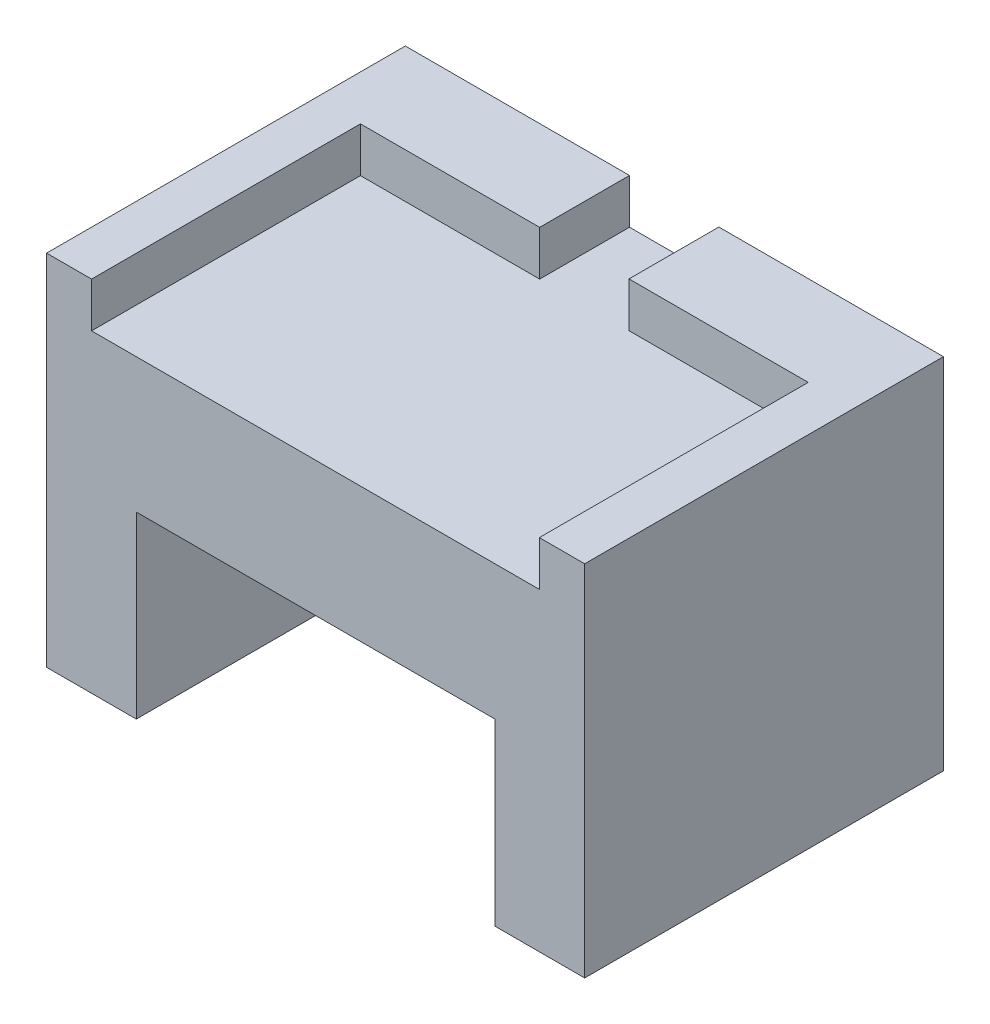
SolidWorks part; units mm, degrees
ref_plane "Front Plane" through (0, 0, 0) normal (0, 0, 1) x (1, 0, 0)
ref_plane "Top Plane" through (0, 0, 0) normal (0, 1, 0) x (1, 0, 0)
ref_plane "Right Plane" through (0, 0, 0) normal (1, 0, 0) x (0, 0, -1)
sketch "Sketch2" plane through (0, 0, 0) normal (0, 0, 1) x (1, 0, 0)
  line L1 (-7.9809, 8.5014) -> (68.2191, 8.5014)
  line L2 (-7.9809, 8.5014) -> (-7.9809, -16.8986)
  line L3 (-7.9809, -16.8986) -> (68.2191, -16.8986)
  line L4 (68.2191, 8.5014) -> (68.2191, -16.8986)
  dimension "D1" = 25.4
  dimension "D2" = 76.2
extrude "Boss-Extrude1" add sketch "Sketch2" along normal blind 50.8
sketch "Sketch3" plane through (0, -16.8986, 0) normal (0, -1, 0) x (1, 0, 0)
  line L0 (-7.9809, 0) -> (68.2191, 0) construction
  line L1 (-7.9809, 50.8) -> (4.7191, 50.8)
  line L2 (-7.9809, 50.8) -> (-7.9809, 0)
  line L3 (-7.9809, 0) -> (4.7191, 0)
  line L4 (4.7191, 50.8) -> (4.7191, 0)
  line L6 (68.2191, 50.8) -> (55.5191, 50.8)
  line L7 (68.2191, 50.8) -> (68.2191, 0)
  line L8 (68.2191, 0) -> (55.5191, 0)
  line L9 (55.5191, 50.8) -> (55.5191, 0)
  dimension "D1" = 12.7
  dimension "D2" = 12.7
extrude "Boss-Extrude2" add sketch "Sketch3" along normal blind 25.4
sketch "Sketch4" plane through (4.7191, 0, 0) normal (1, 0, 0) x (0, 0, -1)
  line L0 (-50.8, -42.2986) -> (-50.8, 8.5014) construction
  line L2 (0, -42.2986) -> (-50.8, -42.2986) construction
  circle A0 centre (-25.4, -29.5986) radius 6.35
  dimension "D1" = 12.7
  dimension "D2" = 25.4
  dimension "D3" = 12.7
extrude "Boss-Extrude3" add sketch "Sketch4" along normal blind 50.8
sketch "Sketch7" plane through (0, 8.5014, 0) normal (0, 1, 0) x (1, 0, 0)
  line L0 (68.2191, -50.8) -> (-7.9809, -50.8) construction
  line L1 (-1.6106, -50.8) -> (61.798, -50.8)
  line L2 (-1.6106, -50.8) -> (-1.6106, -12.7254)
  line L3 (-1.6106, -12.7254) -> (61.798, -12.7254)
  line L4 (61.798, -50.8) -> (61.798, -12.7254)
  line L5 (68.2191, 0) -> (-7.9809, 0) construction
  line L6 (23.7691, -12.7254) -> (36.4183, -12.7254)
  line L7 (23.7691, -12.7254) -> (23.7691, 0)
  line L8 (23.7691, 0) -> (36.4183, 0)
  line L9 (36.4183, -12.7254) -> (36.4183, 0)
  line L10 (-7.9809, -50.8) -> (-7.9809, 0) construction
  line L11 (68.2191, -50.8) -> (68.2191, 0) construction
  line M9 (68.2191, 0) -> (-7.9809, 0)
  line M11 (-7.9809, -50.8) -> (68.2191, -50.8)
  dimension "D1" = 38.0746
  dimension "D2" = 12.6492
  dimension "D3" = 31.75
  dimension "D4" = 31.8008
  dimension "D5" = 25.3797
  dimension "D6" = 25.3797
extrude "Cut-Extrude1" cut sketch "Sketch7" against normal blind 6.35 contours L4 L3 L2 M11 | L3 L9 L7 M9
